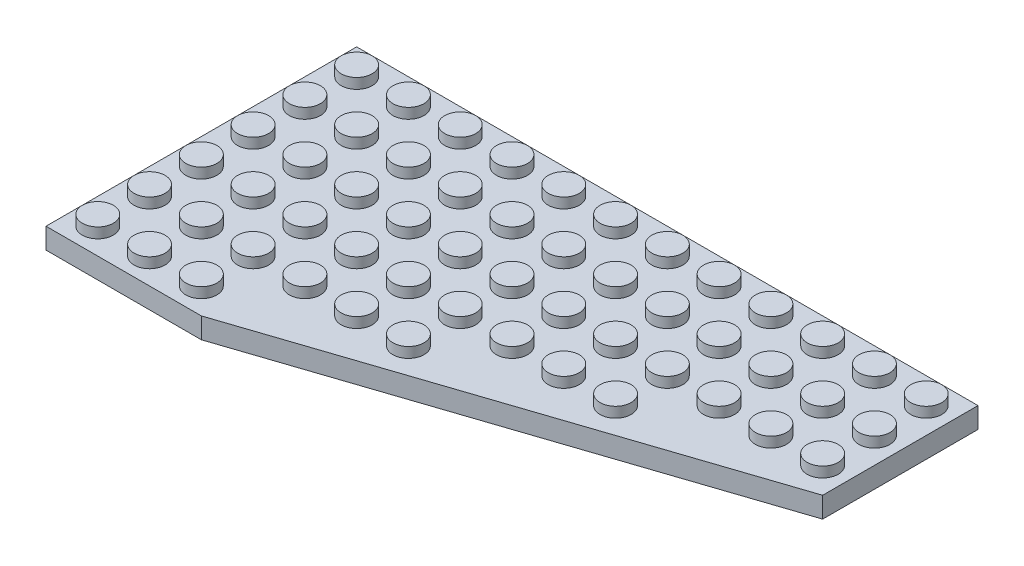
SolidWorks part; units mm, degrees
ref_plane "Front Plane" through (0, 0, 0) normal (0, 0, 1) x (1, 0, 0)
ref_plane "Top Plane" through (0, 0, 0) normal (0, 1, 0) x (1, 0, 0)
ref_plane "Right Plane" through (0, 0, 0) normal (1, 0, 0) x (0, 0, -1)
sketch "Sketch1" plane through (0, 0, 0) normal (0, 1, 0) x (1, 0, 0)
  line L0 (0, 0) -> (96, 0)
  line L1 (96, 0) -> (96, -24)
  line L2 (96, -24) -> (24, -48)
  line L3 (24, -48) -> (0, -48)
  line L4 (0, -48) -> (0, 0)
  dimension "D1" = 96
  dimension "D2" = 24
  dimension "D3" = 48
  dimension "D4" = 24
extrude "Boss-Extrude1" add sketch "Sketch1" along normal blind 3.2
sketch "Sketch2" plane through (0, 3.2, 0) normal (0, 1, 0) x (1, 0, 0)
  line L0 (0, 0) -> (4, 0) construction
  line L1 (96, 0) -> (0, 0) construction
  line L2 (4, 0) -> (4, -4) construction
  circle A0 centre (4, -4) radius 2.4
  dimension "D3" = 4.8
  dimension "D1" = 4
  dimension "D2" = 4
extrude "Boss-Extrude2" add sketch "Sketch2" along normal blind 1.6
pattern_linear "LPattern1" count 12 spacing 8 along (1, 0, 0) count 3 spacing 8 along (0, 0, 1) of "Boss-Extrude2"
sketch "Sketch3" plane through (0, 3.2, 0) normal (0, 1, 0) x (1, 0, 0)
  line L0 (4, -20) -> (4, -28) construction
  circle A0 centre (4, -28) radius 2.4
  dimension "D2" = 4.8
  dimension "D1" = 8
extrude "Boss-Extrude3" add sketch "Sketch3" along normal blind 1.6
pattern_linear "LPattern2" count 9 spacing 8 along (1, 0, 0) of "Boss-Extrude3"
sketch "Sketch4" plane through (0, 3.2, 0) normal (0, 1, 0) x (1, 0, 0)
  line L0 (4, -28) -> (4, -36) construction
  circle A0 centre (4, -36) radius 2.4
  dimension "D2" = 4.8
  dimension "D1" = 8
extrude "Boss-Extrude4" add sketch "Sketch4" along normal blind 1.6
pattern_linear "LPattern3" count 6 spacing 8 along (1, 0, 0) of "Boss-Extrude4"
sketch "Sketch5" plane through (0, 3.2, 0) normal (0, 1, 0) x (1, 0, 0)
  line L0 (4, -36) -> (4, -44) construction
  circle A0 centre (4, -44) radius 2.4
  dimension "D2" = 4.8
  dimension "D1" = 8
extrude "Boss-Extrude5" add sketch "Sketch5" along normal blind 1.6
pattern_linear "LPattern4" count 3 spacing 8 along (1, 0, 0) of "Boss-Extrude5"
shell "Shell1" thickness 1.6
